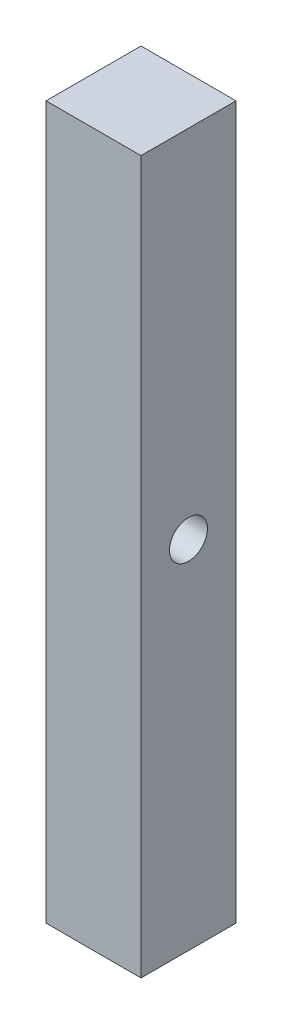
SolidWorks part; units mm, degrees
ref_plane "Front Plane" through (0, 0, 0) normal (0, 0, 1) x (1, 0, 0)
ref_plane "Top Plane" through (0, 0, 0) normal (0, 1, 0) x (1, 0, 0)
ref_plane "Right Plane" through (0, 0, 0) normal (1, 0, 0) x (0, 0, -1)
sketch "Sketch1" plane through (0, 0, 0) normal (0, 1, 0) x (1, 0, 0)
  line L1 (-10, 10) -> (10, 10)
  line L2 (-10, 10) -> (-10, -10)
  line L3 (-10, -10) -> (10, -10)
  line L4 (10, 10) -> (10, -10)
  line L5 (-10, 10) -> (10, -10) construction
  line L6 (-10, -10) -> (10, 10) construction
  point P0 (0, 0)
  dimension "D1" = 20
  dimension "D2" = 20
extrude "Boss-Extrude1" add sketch "Sketch1" along normal blind 150
sketch "Sketch2" plane through (10, 0, 0) normal (1, 0, 0) x (0, 0, -1)
  line L0 (0, 150) -> (0, 0) construction
  line L1 (-10, 150) -> (10, 150) construction
  circle A0 centre (0, 75) radius 4
  dimension "D1" = 8
extrude "Cut-Extrude1" cut sketch "Sketch2" against normal through all both and the other way through all
